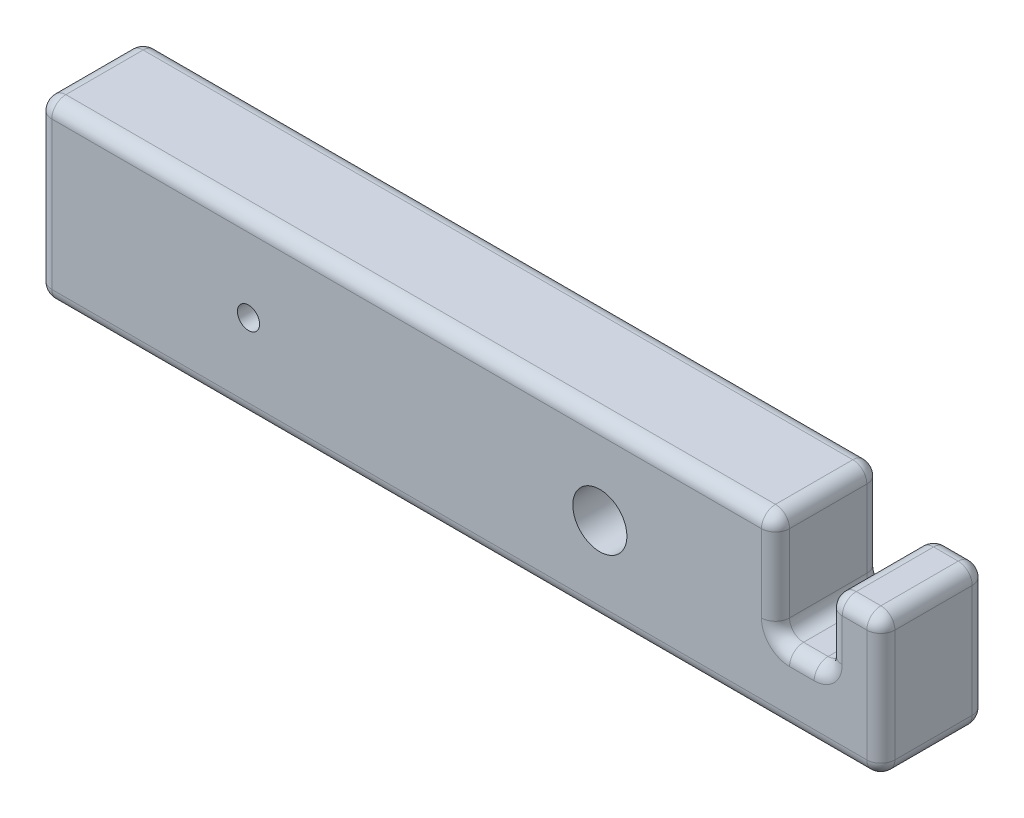
SolidWorks part; units mm, degrees
ref_plane "Front Plane" through (0, 0, 0) normal (0, 0, 1) x (1, 0, 0)
ref_plane "Top Plane" through (0, 0, 0) normal (0, 1, 0) x (1, 0, 0)
ref_plane "Right Plane" through (0, 0, 0) normal (1, 0, 0) x (0, 0, -1)
sketch "Sketch1" plane through (0, 0, 0) normal (0, 0, 1) x (1, 0, 0)
  line L0 (101.6, 15.875) -> (101.6, 31.75)
  line L1 (0, 0) -> (152.4, 0)
  line L2 (0, 0) -> (0, 31.75)
  line L3 (0, 31.75) -> (133.35, 31.75)
  line L4 (152.4, 0) -> (152.4, 25.4)
  line L5 (101.6, 15.875) -> (101.6, 0)
  line L6 (38.1, 15.875) -> (38.1, 31.75)
  line L7 (38.1, 15.875) -> (38.1, 0)
  line L9 (133.35, 31.75) -> (101.6, 31.75)
  line L11 (152.4, 25.4) -> (142.875, 25.4)
  line L12 (133.35, 31.75) -> (133.35, 12.7)
  line L15 (133.35, 12.7) -> (142.875, 12.7)
  line L16 (142.875, 25.4) -> (142.875, 12.7)
  circle A0 centre (101.6, 15.875) radius 4.8895
  circle A1 centre (38.1, 15.875) radius 2
  dimension "D3" = 9.779
  dimension "D6" = 4
  dimension "D1" = 9.525
  dimension "D2" = 31.75
  dimension "D4" = 50.8
  dimension "D5" = 63.5
  dimension "D7" = 9.525
  dimension "D8" = 12.7
  dimension "D9" = 12.7
extrude "Boss-Extrude1" add sketch "Sketch1" along normal blind 19.05 contours A1 L7 L1 L5 A0 L0 L3 L6 | A0 L5 L1 L4 L11 L16 L15 L12 L3 L0 | A1 L6 L3 L2 L1 L7
fillet "Fillet2" radius 2.54 24 edges at (0, 0, 9.525) (76.2, 0, 0) (142.875, 19.05, 0) (0, 15.875, 0) (142.875, 12.7, 9.525) (138.1125, 12.7, 0) (152.4, 0, 9.525) (152.4, 12.7, 0) (152.4, 25.4, 9.525) (142.875, 25.4, 9.525) (147.6375, 25.4, 0) (133.35, 12.7, 9.525) (133.35, 22.225, 0) (133.35, 22.225, 19.05) (138.1125, 12.7, 19.05) (142.875, 19.05, 19.05) (147.6375, 25.4, 19.05) (152.4, 12.7, 19.05) (76.2, 0, 19.05) (0, 15.875, 19.05) (133.35, 31.75, 9.525) (66.675, 31.75, 19.05) (0, 31.75, 9.525) (66.675, 31.75, 0)
